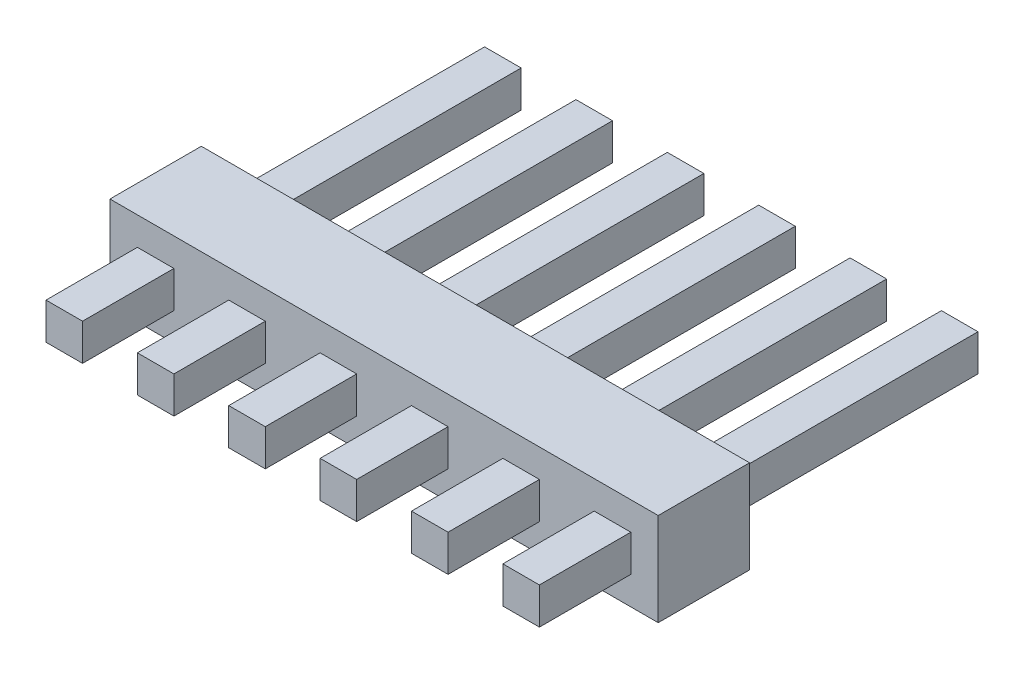
SolidWorks part; units mm, degrees
ref_plane "Спереди" through (0, 0, 0) normal (0, 0, 1) x (1, 0, 0)
ref_plane "Сверху" through (0, 0, 0) normal (0, 1, 0) x (1, 0, 0)
ref_plane "Справа" through (0, 0, 0) normal (1, 0, 0) x (0, 0, -1)
sketch "Эскиз1" plane through (0, 0, 0) normal (0, 0, 1) x (1, 0, 0)
  line L1 (-7.5, -1.27) -> (7.5, -1.27)
  line L2 (-7.5, -1.27) -> (-7.5, 1.27)
  line L3 (-7.5, 1.27) -> (7.5, 1.27)
  line L4 (7.5, -1.27) -> (7.5, 1.27)
  line L5 (-7.5, -1.27) -> (7.5, 1.27) construction
  line L6 (-7.5, 1.27) -> (7.5, -1.27) construction
  point P0 (0, 0)
  dimension "D1" = 2.54
  dimension "D2" = 15
extrude "Бобышка-Вытянуть1" add sketch "Эскиз1" along normal blind 2.5
sketch "Эскиз2" plane through (0, 0, 0) normal (0, 0, -1) x (-1, 0, 0)
  line L0 (-1000, 0) -> (49000, 0) construction
  line L1 (-4.25, -0.5) -> (-3.25, -0.5)
  line L2 (-6.75, -0.5) -> (-5.75, -0.5)
  line L3 (-6.75, -0.5) -> (-6.75, 0.5)
  line L4 (-6.75, 0.5) -> (-5.75, 0.5)
  line L5 (-5.75, -0.5) -> (-5.75, 0.5)
  line L6 (-6.75, -0.5) -> (-5.75, 0.5) construction
  line L7 (-6.75, 0.5) -> (-5.75, -0.5) construction
  line L8 (-4.25, -0.5) -> (-4.25, 0.5)
  line L9 (-4.25, 0.5) -> (-3.25, 0.5)
  line L10 (-3.25, -0.5) -> (-3.25, 0.5)
  line L11 (-4.25, -0.5) -> (-3.25, 0.5) construction
  line L12 (-4.25, 0.5) -> (-3.25, -0.5) construction
  line L13 (-1.75, -0.5) -> (-0.75, -0.5)
  line L14 (-1.75, -0.5) -> (-1.75, 0.5)
  line L15 (-1.75, 0.5) -> (-0.75, 0.5)
  line L16 (-0.75, -0.5) -> (-0.75, 0.5)
  line L17 (-1.75, -0.5) -> (-0.75, 0.5) construction
  line L18 (-1.75, 0.5) -> (-0.75, -0.5) construction
  line L19 (0.75, -0.5) -> (1.75, -0.5)
  line L20 (0.75, -0.5) -> (0.75, 0.5)
  line L21 (0.75, 0.5) -> (1.75, 0.5)
  line L22 (1.75, -0.5) -> (1.75, 0.5)
  line L23 (0.75, -0.5) -> (1.75, 0.5) construction
  line L24 (0.75, 0.5) -> (1.75, -0.5) construction
  line L25 (3.25, -0.5) -> (4.25, -0.5)
  line L26 (3.25, -0.5) -> (3.25, 0.5)
  line L27 (3.25, 0.5) -> (4.25, 0.5)
  line L28 (4.25, -0.5) -> (4.25, 0.5)
  line L29 (3.25, -0.5) -> (4.25, 0.5) construction
  line L30 (3.25, 0.5) -> (4.25, -0.5) construction
  line L31 (5.75, -0.5) -> (6.75, -0.5)
  line L32 (5.75, -0.5) -> (5.75, 0.5)
  line L33 (5.75, 0.5) -> (6.75, 0.5)
  line L34 (6.75, -0.5) -> (6.75, 0.5)
  line L35 (5.75, -0.5) -> (6.75, 0.5) construction
  line L36 (5.75, 0.5) -> (6.75, -0.5) construction
  line L37 (-7.5, -1.27) -> (-7.5, 1.27) construction
  point P1 (-6.25, 0)
  point P10 (-3.75, 0)
  point P15 (-1.25, 0)
  point P20 (1.25, 0)
  point P25 (3.75, 0)
  point P30 (6.25, 0)
  dimension "D1" = 1
  dimension "D2" = 6
  dimension "D3" = 2.5
  dimension "0" = 0.75
extrude "Бобышка-Вытянуть2" add sketch "Эскиз2" along normal blind 7 and the other way blind 5
